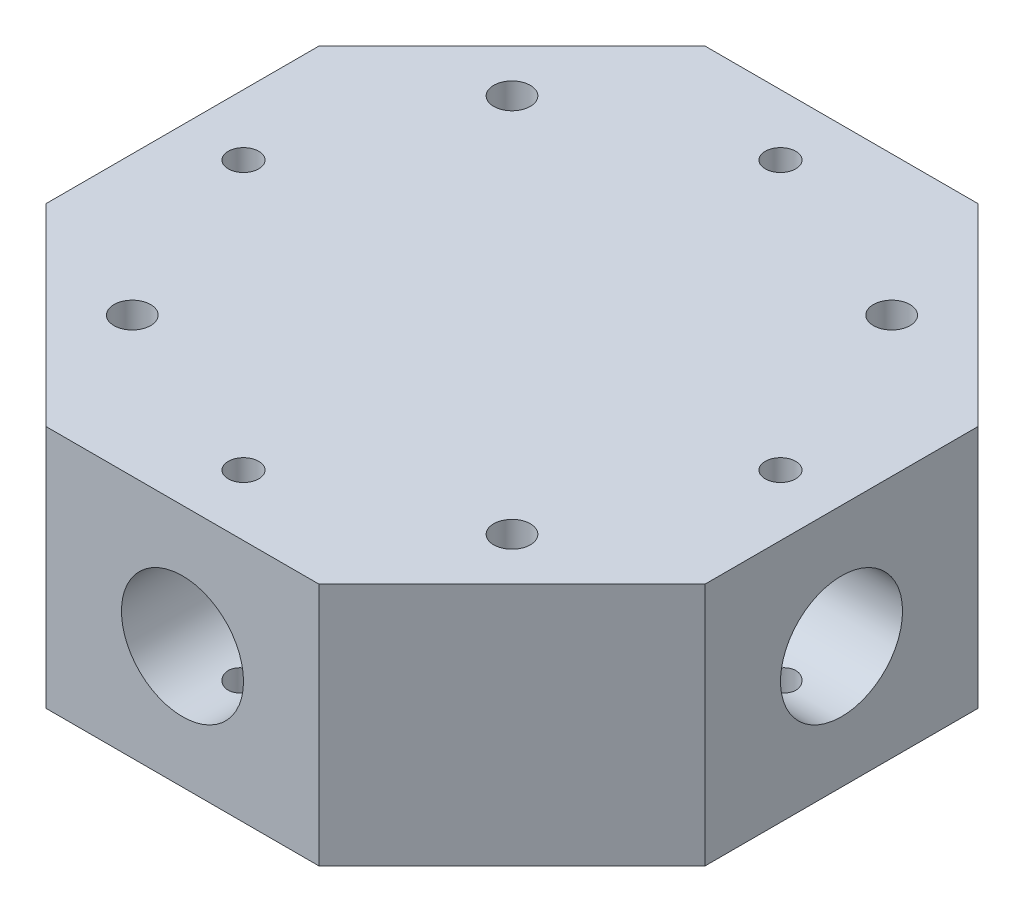
SolidWorks part; units mm, degrees
material "ABS"
ref_plane "Front Plane" through (0, 0, 0) normal (0, 0, 1) x (1, 0, 0)
ref_plane "Top Plane" through (0, 0, 0) normal (0, 1, 0) x (1, 0, 0)
ref_plane "Right Plane" through (0, 0, 0) normal (1, 0, 0) x (0, 0, -1)
sketch "Sketch1" plane through (0, 0, 0) normal (0, 1, 0) x (1, 0, 0)
  line L0 (-124, 125.5) -> (-119.5, 125.5) construction
  line L1 (-124, -124) -> (124, -124) construction
  line L2 (-124, -124) -> (-124, 124) construction
  line L3 (-124, 124) -> (124, 124) construction
  line L4 (124, -124) -> (124, 124) construction
  line L5 (-124, -124) -> (124, 124) construction
  line L6 (-124, 124) -> (124, -124) construction
  line L7 (-125.5, -125.5) -> (125.5, -125.5) construction
  line L8 (-125.5, -125.5) -> (-125.5, 125.5) construction
  line L9 (-125.5, 125.5) -> (125.5, 125.5) construction
  line L10 (125.5, -125.5) -> (125.5, 125.5) construction
  line L11 (-125.5, -125.5) -> (125.5, 125.5) construction
  line L12 (-125.5, 125.5) -> (125.5, -125.5) construction
  line L13 (-121, 125.5) -> (-118, 125.5)
  line L14 (-114, 125.5) -> (-114, 127.5636) construction
  line L15 (-125.5, 110) -> (-134.3044, 110) construction
  line L16 (-110, 125.5) -> (-110, 132.5776) construction
  line L17 (-125.5, 110) -> (-110, 125.5) construction
  line L18 (-125.5, 110) -> (-110, 110) construction
  line L19 (-110, 110) -> (-110, 125.5) construction
  line L28 (-120.4645, -127.5355) -> (127.5355, 120.4645) construction
  line L29 (-127.5355, -120.4645) -> (120.4645, 127.5355) construction
  line L30 (-127.5355, 120.4645) -> (120.4645, -127.5355) construction
  line L31 (-120.4645, 127.5355) -> (127.5355, -120.4645) construction
  line L33 (11.1838, 27) -> (-11.1838, 27)
  line L40 (-11.1838, 27) -> (-27, 11.1838)
  line L41 (-27, 11.1838) -> (-27, -11.1838)
  line L42 (-27, -11.1838) -> (-11.1838, -27)
  line L43 (-11.1838, -27) -> (11.1838, -27)
  line L44 (11.1838, -27) -> (27, -11.1838)
  line L45 (27, -11.1838) -> (27, 11.1838)
  line L46 (27, 11.1838) -> (11.1838, 27)
  circle A0 centre (0, 0) radius 53 construction
  circle A1 centre (0, 0) radius 15 construction
  circle A2 centre (0, 0) radius 22 construction
  circle A3 centre (0, 22) radius 1.25
  circle A4 centre (15.5563, 15.5563) radius 1.5
  circle A5 centre (22, 0) radius 1.25
  circle A6 centre (15.5563, -15.5563) radius 1.5
  circle A7 centre (0, -22) radius 1.25
  circle A8 centre (-15.5563, -15.5563) radius 1.5
  circle A9 centre (-22, 0) radius 1.25
  circle A10 centre (-15.5563, 15.5563) radius 1.5
  point P0 (0, 0)
  point P6 (0, 0)
  point P17 (-119.5, 125.5)
  dimension "D10" = 106
  dimension "D13" = 30
  dimension "D14" = 44
  dimension "D15" = 2.5
  dimension "D21" = 3
  dimension "D11" = 3
  dimension "D12" = 3
  dimension "D16" = 3
  dimension "D22" = 2.5
  dimension "D23" = 2.5
  dimension "D24" = 2.5
  dimension "D1" = 248
  dimension "D2" = 248
  dimension "D3" = 251
  dimension "D4" = 251
  dimension "D5" = 4.5
  dimension "D6" = 3
  dimension "D7" = 10
  dimension "D8" = 14
  dimension "D9" = 14
  dimension "D17" = 5
  dimension "D18" = 5
  dimension "D19" = 5
  dimension "D20" = 5
extrude "Boss-Extrude1" add sketch "Sketch1" along normal mid plane 20
sketch "Sketch7" plane through (0, 0, 27) normal (0, 0, 1) x (1, 0, 0)
  circle A0 centre (0, 0) radius 5
  dimension "D1" = 10
extrude "Cut-Extrude4" cut sketch "Sketch7" against normal up to surface (54 mm away) up to face at (0, 0, -27)
sketch "Sketch8" plane through (27, 0, 0) normal (1, 0, 0) x (0, 0, -1)
  circle A0 centre (0, 0) radius 5
  dimension "D1" = 10
extrude "Cut-Extrude5" cut sketch "Sketch8" against normal up to surface (54 mm away) up to face at (-27, 0, 0)
